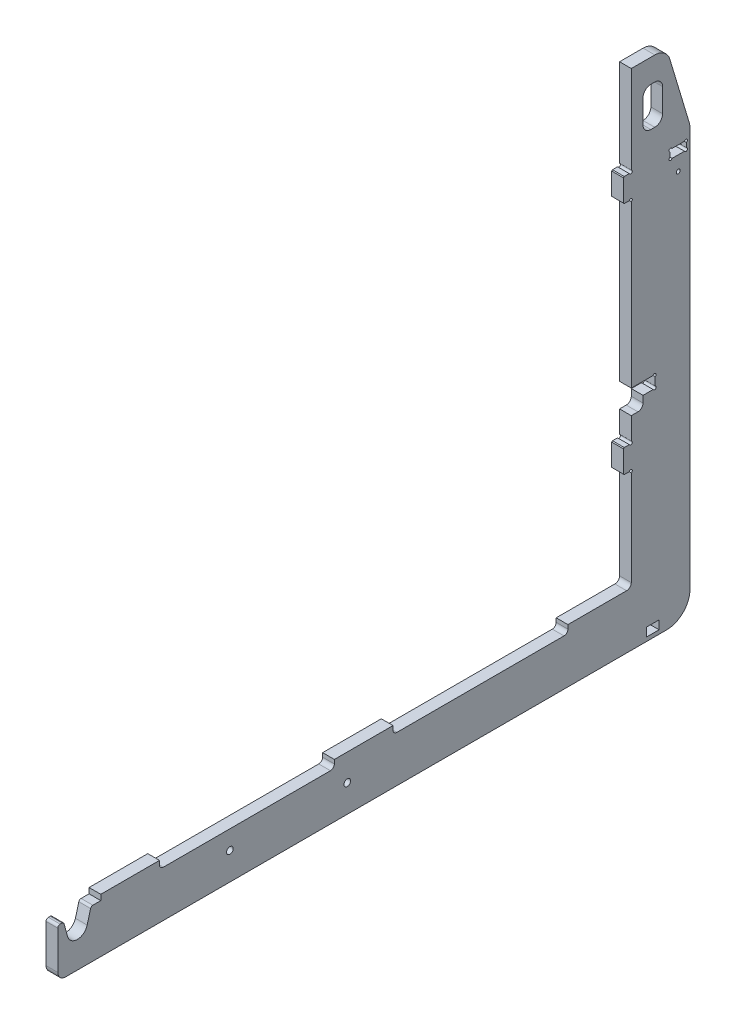
SolidWorks part; units mm, degrees
material "S355J2H"
ref_plane "Front Plane" through (0, 0, 0) normal (0, 0, 1) x (1, 0, 0)
ref_plane "Top Plane" through (0, 0, 0) normal (0, 1, 0) x (1, 0, 0)
ref_plane "Right Plane" through (0, 0, 0) normal (1, 0, 0) x (0, 0, -1)
sketch "Sketch1" plane through (0, 0, 0) normal (1, 0, 0) x (0, 0, -1)
  line L0 (-678, 0) -> (0, 0)
  line L1 (0, 0) -> (0, 460)
  line L2 (-678, 0) -> (-678, -69)
  line L4 (-678, -69) -> (75, -69)
  line L5 (75, -69) -> (75, 460)
  line L6 (75, 460) -> (0, 460)
  dimension "D1" = 678
  dimension "D2" = 460
  dimension "D3" = 75
  dimension "D4" = 69
extrude "Boss-Extrude1" add sketch "Sketch1" along normal blind 15
fillet "Fillet1" radius 30 1 edges at (7.5, -69, -75)
sketch "Sketch2" plane through (15, 0, 0) normal (1, 0, 0) x (0, 0, -1)
  line L0 (35, 331) -> (35, 61) construction
  line L1 (75, -39) -> (75, 460) construction
  line L2 (-678, -69) -> (45, -69) construction
  circle A0 centre (35, 331) radius 17.6
  circle A1 centre (35, 61) radius 17.6
  dimension "D1" = 35.2
  dimension "D2" = 40
  dimension "D3" = 130
  dimension "D4" = 400
extrude "Cut-Extrude1" [suppressed] cut sketch "Sketch2" against normal through all
fillet "Fillet2" radius 6 1 edges at (7.5, 0, 0)
sketch "Sketch3" plane through (0, 0, 0) normal (-1, 0, 0) x (0, 0, 1)
  line L0 (0, 460) -> (0, 6) construction
  line L1 (0, 221.25) -> (-30.5, 221.25)
  line L2 (0, 221.25) -> (0, 205.75)
  line L3 (0, 205.75) -> (-30.5, 205.75)
  line L4 (-30.5, 221.25) -> (-30.5, 205.75)
  line L5 (678, -69) -> (-45, -69) construction
  dimension "D1" = 15.5
  dimension "D2" = 30.5
  dimension "D3" = 290.25
extrude "Cut-Extrude2" cut sketch "Sketch3" against normal through all
sketch "Sketch6" plane through (0, 0, 0) normal (0, 0, 1) x (1, 0, 0)
  line L0 (15, 460) -> (15, 221.25) construction
  line L1 (0, 460) -> (15, 460)
  line L2 (0, 460) -> (0, 430)
  line L3 (0, 430) -> (15, 430)
  line L4 (15, 460) -> (15, 430)
  line L5 (0, 205.75) -> (0, 6) construction
  line L6 (0, 160) -> (15, 160)
  line L7 (0, 160) -> (0, 130)
  line L8 (0, 130) -> (15, 130)
  line L9 (15, 160) -> (15, 130)
  line L10 (15, 205.75) -> (15, 6) construction
  point P15 (7.5, 460)
  dimension "D1" = 30
  dimension "D2" = 300
extrude "Boss-Extrude2" add sketch "Sketch6" along normal blind 10
sketch "Sketch7" plane through (0, 0, 0) normal (-1, 0, 0) x (0, 0, 1)
  line L0 (-30.5, 205.75) -> (0, 205.75) construction
  line L1 (0, 205.75) -> (-15, 205.75)
  line L2 (0, 205.75) -> (0, 190.75)
  line L3 (0, 190.75) -> (-15, 190.75)
  line L4 (-15, 205.75) -> (-15, 190.75)
  line L5 (0, 205.75) -> (0, 160) construction
  dimension "D1" = 15
extrude "Cut-Extrude5" cut sketch "Sketch7" against normal through all
fillet "Fillet4" radius 6.5 1 edges at (7.5, 190.75, -15)
sketch "Sketch9" plane through (15, 0, 0) normal (1, 0, 0) x (0, 0, -1)
  line L0 (75, 460) -> (-10, 460) construction
  line L1 (0, 460) -> (75, 460)
  line L2 (0, 460) -> (0, 575)
  line L3 (0, 575) -> (75, 575)
  line L4 (75, 460) -> (75, 575)
  line L5 (75, -39) -> (75, 460) construction
  line L6 (0, 430) -> (0, 221.25) construction
  dimension "D1" = 115
extrude "Boss-Extrude3" add sketch "Sketch9" against normal blind 15
sketch "Sketch8" plane through (15, 0, 0) normal (1, 0, 0) x (0, 0, -1)
  line L1 (49.5, 460.5) -> (70.5, 460.5)
  line L2 (49.5, 460.5) -> (49.5, 449.5)
  line L3 (49.5, 449.5) -> (70.5, 449.5)
  line L4 (70.5, 460.5) -> (70.5, 449.5)
  line L5 (75, -39) -> (75, 575) construction
  line L7 (0, 460) -> (-10, 460) construction
  dimension "D1" = 4.5
  dimension "D2" = 21
  dimension "D3" = 11
  dimension "D4" = 0.5
extrude "Cut-Extrude6" cut sketch "Sketch8" against normal through all
sketch "Sketch10" plane through (15, 0, 0) normal (1, 0, 0) x (0, 0, -1)
  line L0 (45, 575) -> (75, 475)
  line L1 (75, 575) -> (0, 575) construction
  line L2 (75, -39) -> (75, 575) construction
  line L3 (75, 475) -> (75, 575)
  line L4 (75, 575) -> (45, 575)
  dimension "D1" = 30
  dimension "D2" = 100
extrude "Cut-Extrude7" cut sketch "Sketch10" against normal blind 15
sketch "Sketch11" plane through (15, 0, 0) normal (1, 0, 0) x (0, 0, -1)
  line L1 (15, 545) -> (40, 545)
  line L2 (15, 545) -> (15, 495)
  line L3 (15, 495) -> (40, 495)
  line L4 (40, 545) -> (40, 495)
  line L5 (0, 575) -> (0, 460) construction
  line L6 (45, 575) -> (0, 575) construction
  dimension "D1" = 25
  dimension "D2" = 50
  dimension "D3" = 15
  dimension "D4" = 30
extrude "Cut-Extrude8" cut sketch "Sketch11" against normal blind 15
sketch "Sketch5" plane through (0, 0, 0) normal (-1, 0, 0) x (0, 0, 1)
  line L0 (678, -69) -> (-45, -69) construction
  line L1 (-75, -39) -> (-75, 475) construction
  circle A0 centre (-60, 431) radius 2.5
  dimension "D1" = 500
  dimension "D3" = 5
  dimension "D2" = 15
extrude "Cut-Extrude4" cut sketch "Sketch5" against normal through all
cosmetic thread "Cosmetic Thread1" parameters "D2"=6
fillet "Fillet5" radius 20 2 edges at (7.5, 475, -75) (7.5, 575, -45)
fillet "Fillet6" radius 10 4 edges at (7.5, 495, -40) (7.5, 545, -40) (7.5, 545, -15) (7.5, 495, -15)
chamfer "Chamfer1" distance 1 angle 45 4 edges at (7.5, 130, 10) (7.5, 160, 10) (7.5, 430, 10) (7.5, 460, 10)
sketch "Sketch12" plane through (15, 0, 0) normal (1, 0, 0) x (0, 0, -1)
  line L0 (-678, -69) -> (45, -69) construction
  line L1 (35.5, -64) -> (19.5, -64)
  line L2 (35.5, -64) -> (35.5, -53)
  line L3 (35.5, -53) -> (19.5, -53)
  line L4 (19.5, -64) -> (19.5, -53)
  line L5 (75, -39) -> (75, 472.0646) construction
  dimension "D1" = 5
  dimension "D2" = 39.5
  dimension "D3" = 16
  dimension "D4" = 11
extrude "Cut-Extrude9" cut sketch "Sketch12" against normal through all
sketch "Sketch13" plane through (15, 0, 0) normal (1, 0, 0) x (0, 0, -1)
  line L1 (-6, 0) -> (-678, 0) construction
  line L2 (0, 13) -> (0, 6)
  line L3 (-6, 0) -> (-40, 0)
  line L4 (-40, 0) -> (-40, -10)
  line L5 (-40, -10) -> (10, -10)
  line L6 (10, -10) -> (10, 13)
  line L7 (10, 13) -> (0, 13)
  arc A0 (-6, 0) -> (0, 6) centre (-6, 6) ccw construction
  arc A1 (-6, 0) -> (0, 6) centre (-6, 6) ccw
  dimension "D1" = 10
  dimension "D2" = 10
  dimension "D3" = 13
  dimension "D4" = 40
extrude "Cut-Extrude10" [suppressed] cut sketch "Sketch13" against normal through all
fillet "Fillet7" [suppressed] radius 10
sketch "Sketch14" plane through (15, 0, 0) normal (1, 0, 0) x (0, 0, -1)
  line L0 (-6, 0) -> (-678, 0) construction
  line L1 (-603, 0) -> (-379.5, 0)
  line L2 (-603, 0) -> (-603, -10)
  line L3 (-603, -10) -> (-379.5, -10)
  line L4 (-379.5, 0) -> (-379.5, -10)
  line L5 (-678, 0) -> (-678, -69) construction
  line L6 (-342, 0) -> (-342, -251.7036) construction
  line L7 (-304.5, 0) -> (-304.5, -10)
  line L8 (-81, -10) -> (-304.5, -10)
  line L9 (-81, 0) -> (-81, -10)
  line L10 (-81, 0) -> (-304.5, 0)
  dimension "D1" = 75
  dimension "D2" = 10
  dimension "D3" = 75
extrude "Cut-Extrude11" cut sketch "Sketch14" against normal up to surface (15 mm away) up to face at (0, -58.5, -27.5)
fillet "Fillet8" radius 5 4 edges at (7.5, -10, 81) (7.5, -10, 304.5) (7.5, -10, 379.5) (7.5, -10, 603)
sketch "Sketch15" plane through (15, 0, 0) normal (1, 0, 0) x (0, 0, -1)
  line L0 (-0.7071, 129.2929) -> (0, 130) construction
  line L1 (-9, 130) -> (0, 130) construction
  line L2 (-10, 145) -> (26.1827, 145) construction
  line L3 (-10, 131) -> (-10, 159) construction
  line L4 (-0.7071, 160.7071) -> (0, 160) construction
  line L5 (0, 295) -> (139.6761, 295) construction
  line L6 (0, 430) -> (0, 221.25) construction
  line L7 (-0.7071, 429.2929) -> (0, 430) construction
  line L8 (-10, 445) -> (26.1827, 445) construction
  line L9 (-0.7071, 460.7071) -> (0, 460) construction
  line L10 (-10, 431) -> (-10, 459) construction
  circle A0 centre (-0.7071, 129.2929) radius 2
  circle A1 centre (-0.7071, 160.7071) radius 2
  circle A2 centre (-0.7071, 429.2929) radius 2
  circle A3 centre (-0.7071, 460.7071) radius 2
  dimension "D2" = 4
  dimension "D1" = 1
  dimension "D3" = 45
extrude "Cut-Extrude12" cut sketch "Sketch15" against normal through all
sketch "Sketch16" plane through (15, 0, 0) normal (1, 0, 0) x (0, 0, -1)
  line L0 (50.2071, 450.2071) -> (49.5, 449.5) construction
  line L3 (49.5, 449.5) -> (70.5, 449.5) construction
  line L4 (49.5, 455) -> (60, 455) construction
  line L5 (49.5, 460.5) -> (49.5, 449.5) construction
  line L6 (60, 455) -> (60, 449.5) construction
  line L7 (50.2071, 459.7929) -> (49.5, 460.5) construction
  line L8 (69.7929, 459.7929) -> (70.5, 460.5) construction
  line L9 (69.7929, 450.2071) -> (70.5, 449.5) construction
  circle A0 centre (50.2071, 450.2071) radius 2
  circle A1 centre (50.2071, 459.7929) radius 2
  circle A2 centre (69.7929, 459.7929) radius 2
  circle A3 centre (69.7929, 450.2071) radius 2
  dimension "D2" = 4
  dimension "D1" = 45
  dimension "D3" = 1
extrude "Cut-Extrude13" cut sketch "Sketch16" against normal through all
sketch "Sketch17" plane through (15, 0, 0) normal (1, 0, 0) x (0, 0, -1)
  line L0 (29.7929, 206.4571) -> (30.5, 205.75) construction
  line L1 (30.5, 221.25) -> (30.5, 205.75) construction
  line L2 (30.5, 213.5) -> (18.6017, 213.5) construction
  line L3 (29.7929, 220.5429) -> (30.5, 221.25) construction
  circle A0 centre (29.7929, 206.4571) radius 2
  circle A1 centre (29.7929, 220.5429) radius 2
  dimension "D2" = 4
  dimension "D1" = 1
  dimension "D3" = 45
extrude "Cut-Extrude14" cut sketch "Sketch17" against normal through all
sketch "Sketch18" plane through (15, 0, 0) normal (1, 0, 0) x (0, 0, -1)
  line L0 (-678, -69) -> (-733, -69)
  line L1 (-733, -69) -> (-733, -7)
  line L2 (-733, -7) -> (-725.5, -7)
  line L3 (-725.5, -7) -> (-720.5532, -25.3788)
  line L4 (-720.5532, -25.3788) -> (-695.4468, -25.3788) construction
  line L5 (-695.4468, -25.3788) -> (-690.5, -7)
  line L6 (-690.5, -7) -> (-678, -7)
  line L7 (-678, -7) -> (-678, -69)
  line L8 (-678, 0) -> (-678, -69) construction
  line L9 (-603, 0) -> (-678, 0) construction
  arc A0 (-720.5532, -25.3788) -> (-695.4468, -25.3788) centre (-708, -22) ccw
  dimension "D1" = 55
  dimension "D3" = 13
  dimension "D2" = 25
  dimension "D4" = 15
  dimension "D5" = 35
  dimension "D6" = 7
extrude "Boss-Extrude4" add sketch "Sketch18" against normal blind 15
fillet "Fillet9" radius 10 1 edges at (7.5, -69, 733)
fillet "Fillet10" radius 3 3 edges at (7.5, -7, 733) (7.5, -7, 725.5) (7.5, -7, 690.5)
sketch "Sketch19" plane through (15, 0, 0) normal (1, 0, 0) x (0, 0, -1)
  line L0 (-513, -34) -> (-363, -34) construction
  line L1 (-723, -69) -> (45, -69) construction
  line L2 (-733, -10) -> (-733, -59) construction
  circle A0 centre (-513, -34) radius 4.25
  circle A1 centre (-363, -34) radius 4.25
  dimension "D1" = 8.5
  dimension "D2" = 150
  dimension "D3" = 35
  dimension "D4" = 220
extrude "Cut-Extrude15" cut sketch "Sketch19" against normal through all
